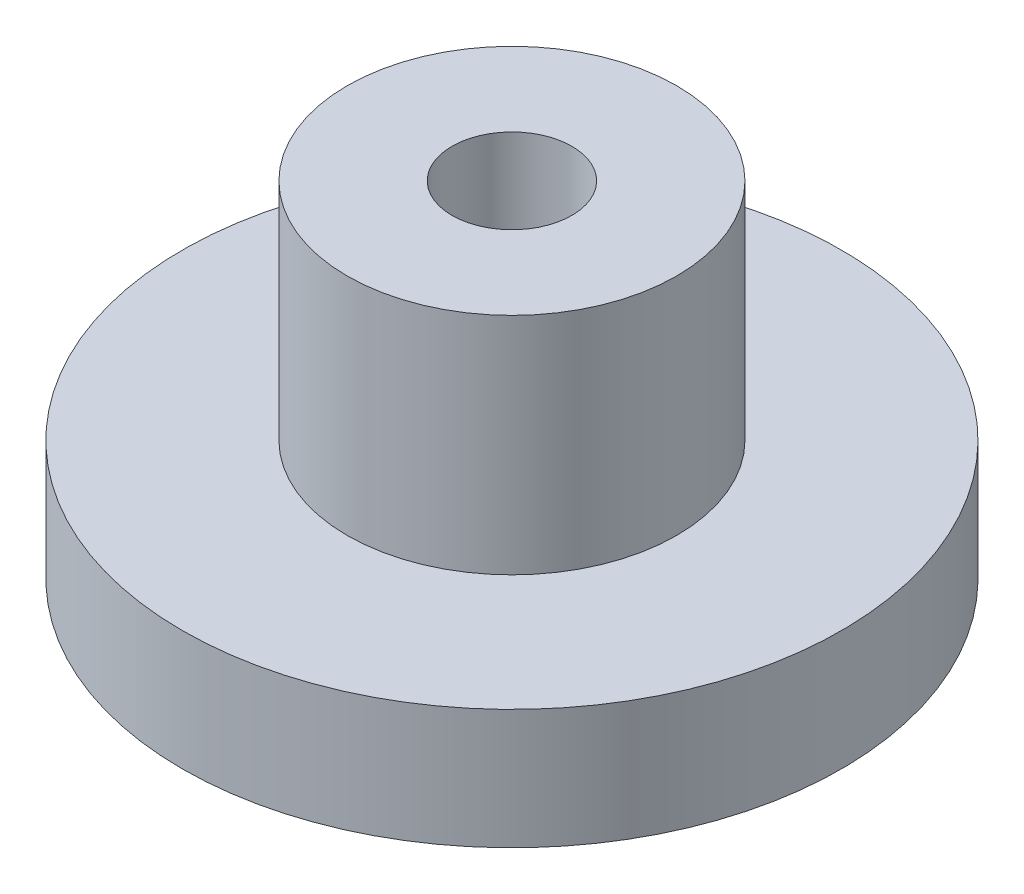
SolidWorks part; units mm, degrees
ref_plane "前视基准面" through (0, 0, 0) normal (0, 0, 1) x (1, 0, 0)
ref_plane "上视基准面" through (0, 0, 0) normal (0, 1, 0) x (1, 0, 0)
ref_plane "右视基准面" through (0, 0, 0) normal (1, 0, 0) x (0, 0, -1)
other "Configuration Table"
sketch "草图1" plane through (0, 0, 0) normal (1, 0, 0) x (0, 0, -1)
  line L1 (0, 0) -> (5.5, 0)
  line L2 (0, 0) -> (0, -7.5)
  line L3 (0, -7.5) -> (5.5, -7.5)
  line L4 (5.5, 0) -> (5.5, -7.5)
  line L5 (0, -7.5) -> (11, -7.5)
  line L6 (0, -7.5) -> (0, -11.5)
  line L7 (0, -11.5) -> (11, -11.5)
  line L8 (11, -7.5) -> (11, -11.5)
  line L9 (0, -11.5) -> (3.1, -11.5)
  line L10 (0, -11.5) -> (0, -8.9)
  line L11 (0, -8.9) -> (3.1, -8.9)
  line L12 (3.1, -11.5) -> (3.1, -8.9)
  line L13 (0, 0) -> (2, 0)
  line L14 (0, 0) -> (0, -8.9)
  line L15 (0, -8.9) -> (2, -8.9)
  line L16 (2, 0) -> (2, -8.9)
  dimension "D1" = 7.5
  dimension "D2" = 2.6
  dimension "D3" = 4
  dimension "D4" = 2
  dimension "D5" = 3.1
  dimension "D6" = 5.5
  dimension "D7" = 11
  dimension "D8" = 5.5
revolve "旋转1" add sketch "草图1" angle 360 about L2
